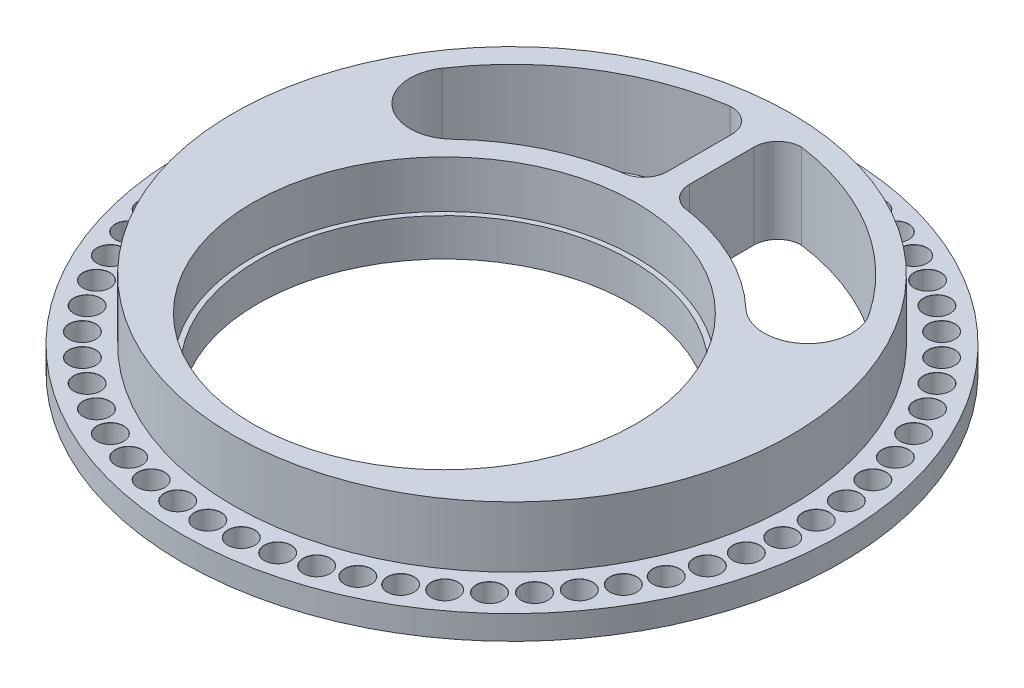
SolidWorks part; units mm, degrees
material "7075-T6, Plate (SS)"
ref_plane "X-Y Datum" through (0, 0, 0) normal (0, 0, 1) x (1, 0, 0)
ref_plane "X-Z Datum" through (0, 0, 0) normal (0, 1, 0) x (1, 0, 0)
ref_plane "Y-Z Datum" through (0, 0, 0) normal (1, 0, 0) x (0, 0, -1)
sketch "Sketch1" plane through (0, 0, 0) normal (0, 1, 0) x (1, 0, 0)
  line L0 (0, 0) -> (0, -12.7) construction
  line L1 (0, -43.0151) -> (0, 43.0151) construction
  line L2 (0, 61.9125) -> (0, 52.3875)
  circle A0 centre (0, -12.7) radius 35.052
  circle A1 centre (0, 0) radius 52.3875 construction
  circle A2 centre (0, 0) radius 57.15 construction
  circle A3 centre (0, 0) radius 61.9125
  point P12 (0, 57.15)
  dimension "D2" = 70.104
  dimension "D3" = 104.775
  dimension "D4" = 123.825
  dimension "D5" = 114.3
  dimension "D1" = 12.7
extrude "Boss-Extrude1" add sketch "Sketch1" along normal blind 4.5212
sketch "Sketch3" plane through (0, 4.5212, 0) normal (0, 1, 0) x (1, 0, 0)
  circle A0 centre (0, 0) radius 52.3875 construction
  circle A1 centre (0, 0) radius 52.3875
extrude "Boss-Extrude2" add sketch "Sketch3" along normal blind 11.43
sketch "Sketch4" plane through (0, 0, 0) normal (0, -1, 0) x (1, 0, 0)
  circle A0 centre (0, 12.7) radius 35.052 construction
  circle A1 centre (0, 12.7) radius 35.052
extrude "Cut-Extrude1" cut sketch "Sketch4" against normal through all
sketch "Sketch9" plane through (0, 15.9512, 0) normal (0, 1, 0) x (1, 0, 0)
  circle A0 centre (0, -12.7) radius 35.052 construction
  circle A1 centre (0, -12.7) radius 35.052 construction
  circle A2 centre (0, -12.7) radius 36
  dimension "D1" = 72
extrude "Cut-Extrude3" cut sketch "Sketch9" against normal blind 8.89
hole_wizard "Ø5.0mm Dowel Hole1" positions "Sketch7" profile "Sketch8" hole size "Ø5.0" standard "ANSI Metric" end condition through all
sketch "Sketch7" plane through (0, 4.5212, 0) normal (0, 1, 0) x (1, 0, 0)
  point P0 (0, 57.15)
sketch "Sketch8" plane through (0, 4.5212, -57.15) normal (1, 0, 0) x (0, 0, 1)
  line L0 (0, 0) -> (0, 4.5212)
  line L1 (0, 4.5212) -> (2.5, 4.5212)
  line L2 (2.5, 4.5212) -> (2.5, 0.025)
  line L3 (2.5, 0.025) -> (2.525, 0)
  line L5 (2.525, 0) -> (0, 0)
  line L6 (-2.5, 0.025) -> (-2.525, 0) construction
  line L11 (0, -6.35) -> (0, 107.95) construction
  dimension "Thru Hole Dia." = 5
  dimension "Thru Hole Depth" = 4.5212
  dimension "Near C'Sink Dia." = 5.05
  dimension "Near C'Sink Angle" = 90
pattern_circular "CirPattern1" count 60 over 360 about axis through (0, 0, 0) along (0, 1, 0) of "Ø5.0mm Dowel Hole1"
sketch "Sketch10" plane through (0, 15.9512, 0) normal (0, 1, 0) x (1, 0, 0)
  circle A0 centre (0, 0) radius 52.3875 construction
  circle A1 centre (0, 0) radius 52.3875 construction
  circle A3 centre (-33.2491, 22.3603) radius 8.255 construction
  circle A4 centre (33.2491, 22.3603) radius 8.255 construction
  arc A9 (0, -52.764) -> (0, 27.364) centre (0, -12.7) ccw construction
  arc A10 (0, 27.364) -> (0, -52.764) centre (0, -12.7) ccw construction
  circle A29 centre (0, 0) radius 48.3235 construction
  arc A30 (-27.5687, 16.3704) -> (27.5687, 16.3704) centre (0, -12.7) cw
  arc A31 (-40.0992, 26.967) -> (40.0992, 26.967) centre (0, 0) cw
  arc A32 (-40.0992, 26.967) -> (-27.5687, 16.3704) centre (-33.2491, 22.3603) ccw
  arc A33 (27.5687, 16.3704) -> (40.0992, 26.967) centre (33.2491, 22.3603) ccw
  point P21 (0, 0)
  point P22 (0, 0)
  point P23 (0, 0)
  dimension "D3" = 16.51
  dimension "D4" = 96.647
  dimension "D5" = 12.7
  dimension "D1" = 40.064
  dimension "D2" = 40.064
extrude "Cut-Extrude5" cut sketch "Sketch10" against normal through all contours A33 A31 A32 A30
ref_plane "Plane2" through (0, 7.9756, 0) normal (0, 1, 0) x (1, 0, 0)
sketch "Sketch15" plane through (0, 7.9756, 0) normal (0, 1, 0) x (1, 0, 0)
  line L1 (-2.1171, 31.2835) -> (-2.1171, 43.3958)
  line L4 (2.032, 31.291) -> (2.032, 43.4389)
  line L6 (-2.1764, 48.3235) -> (-2.1667, 48.2749) construction
  line L8 (2.1667, 48.2749) -> (2.1764, 48.3235) construction
  arc A0 (27.5687, 16.3704) -> (-27.5687, 16.3704) centre (0, -12.7) ccw construction
  arc A1 (27.5687, 16.3704) -> (-27.5687, 16.3704) centre (0, -12.7) ccw construction
  arc A2 (40.0992, 26.967) -> (-40.0992, 26.967) centre (0, 0) ccw construction
  arc A3 (-2.1171, 43.3958) -> (-6.9062, 47.8275) centre (-6.5621, 43.3958) ccw
  arc A4 (40.0992, 26.967) -> (-40.0992, 26.967) centre (0, 0) ccw construction
  arc A5 (6.5037, 47.8838) -> (2.032, 43.4389) centre (6.477, 43.4389) ccw
  arc A7 (-2.1171, 31.2835) -> (-5.362, 27.0036) centre (-6.5621, 31.2835) cw
  arc A9 (2.032, 31.291) -> (5.2509, 27.0184) centre (6.477, 31.291) ccw
  arc A10 (-6.9062, 47.8275) -> (6.5037, 47.8838) centre (0, 0) cw
  arc A11 (-5.362, 27.0036) -> (5.2509, 27.0184) centre (0, -12.7) cw
  point P4 (0, 0)
  point P9 (0, 37.4715)
  dimension "D1" = 4.445
  dimension "D2" = 2.1171
  dimension "D3" = 4.445
  dimension "D4" = 2.032
  dimension "D5" = 43.4389
  dimension "D6" = 31.2835
  dimension "D8" = 12.148
  dimension "D9" = 12.1123
extrude "Boss-Extrude3" add sketch "Sketch15" along normal up to surface and the other way up to surface contours A9 L4 A5 A10 A3 L1 A7 A11 up to face at (0, 15.9512, -26.9504) other way up to face at (0, 0, -26.9504)
ref_point "Point1"
ref_plane "Plane1" through (0, 0, 0) normal (1, 0, 0) x (0, 0, -1)
split line "Split Line1" [suppressed]
sketch "Sketch14" plane through (0, 7.9756, 0) normal (0, 1, 0) x (1, 0, 0)
  circle A0 centre (-33.2491, 22.3603) radius 8.255
ref_point "Point4"
sketch "Sketch20" plane through (0, 4.5212, 0) normal (0, 1, 0) x (1, 0, 0)
  circle A0 centre (0, 0) radius 52.3875
  circle A2 centre (0, 0) radius 66.6087
sketch "Sketch25" plane through (0, 15.9512, 0) normal (0, 1, 0) x (1, 0, 0)
  line L6 (-4.6571, 31.2835) -> (-4.6571, 43.3958)
  line L7 (-4.6571, 31.2835) -> (-4.6571, 43.3958)
  line L12 (4.572, 43.4389) -> (4.572, 31.291)
  line L13 (4.572, 43.4389) -> (4.572, 31.291)
  circle A1 centre (-51.685, -7.6867) radius 0.134
  circle A2 centre (49.3335, -18.9489) radius 0.46
  arc A3 (48.8818, -18.8622) -> (48.9404, -18.71) centre (-0.2183, 0.1504) ccw
  arc A4 (48.8818, -18.8622) -> (48.9404, -18.71) centre (-0.2183, 0.1504) ccw
  arc A45 (-4.6571, 43.3958) -> (-6.6423, 45.2991) centre (-6.5621, 43.3958) ccw
  arc A46 (-5.9167, 29.4912) -> (-4.6571, 31.2835) centre (-6.5621, 31.2835) ccw
  arc A47 (-5.9167, 29.4912) -> (-29.3165, 18.2135) centre (0, -12.7) ccw
  arc A48 (-37.9914, 25.5495) -> (-29.3165, 18.2135) centre (-33.2491, 22.3603) ccw
  arc A49 (-6.6423, 45.2991) -> (-37.9914, 25.5495) centre (0, 0) ccw
  arc A50 (-4.6571, 43.3958) -> (-6.6423, 45.2991) centre (-6.5621, 43.3958) ccw
  arc A51 (-5.9167, 29.4912) -> (-4.6571, 31.2835) centre (-6.5621, 31.2835) ccw
  arc A52 (-5.9167, 29.4912) -> (-29.3165, 18.2135) centre (0, -12.7) ccw
  arc A53 (-37.9914, 25.5495) -> (-29.3165, 18.2135) centre (-33.2491, 22.3603) ccw
  arc A54 (-6.6423, 45.2991) -> (-37.9914, 25.5495) centre (0, 0) ccw
  circle A68 centre (-0.2183, 0.1504) radius 52.1224
  circle A69 centre (0, -12.7) radius 32.512
  circle A70 centre (0, -12.7) radius 32.512
  arc A72 (29.3165, 18.2135) -> (37.9914, 25.5495) centre (33.2491, 22.3603) ccw
  arc A73 (4.572, 31.291) -> (5.8124, 29.5056) centre (6.477, 31.291) ccw
  arc A74 (29.3165, 18.2135) -> (5.8124, 29.5056) centre (0, -12.7) ccw
  arc A75 (37.9914, 25.5495) -> (6.3564, 45.3401) centre (0, 0) ccw
  arc A76 (6.3564, 45.3401) -> (4.572, 43.4389) centre (6.477, 43.4389) ccw
  arc A77 (29.3165, 18.2135) -> (37.9914, 25.5495) centre (33.2491, 22.3603) ccw
  arc A78 (4.572, 31.291) -> (5.8124, 29.5056) centre (6.477, 31.291) ccw
  arc A79 (29.3165, 18.2135) -> (5.8124, 29.5056) centre (0, -12.7) ccw
  arc A80 (37.9914, 25.5495) -> (6.3564, 45.3401) centre (0, 0) ccw
  arc A81 (6.3564, 45.3401) -> (4.572, 43.4389) centre (6.477, 43.4389) ccw
  dimension "D1" = 2.54
  dimension "D2" = 2.54
  dimension "D3" = 2.54
extrude "Boss-Extrude5" [suppressed] add sketch "Sketch25" along normal blind 1.27
